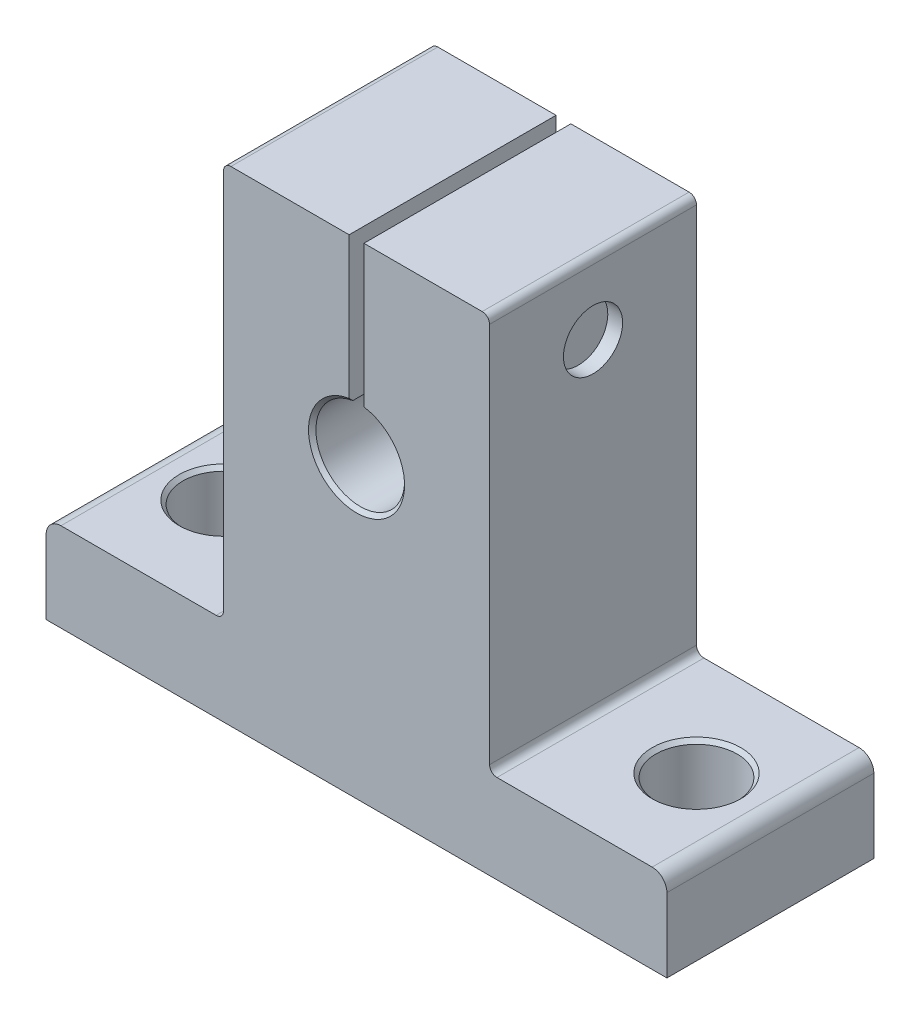
SolidWorks part; units mm, degrees
ref_plane "Front Plane" through (0, 0, 0) normal (0, 0, 1) x (1, 0, 0)
ref_plane "Top Plane" through (0, 0, 0) normal (0, 1, 0) x (1, 0, 0)
ref_plane "Right Plane" through (0, 0, 0) normal (1, 0, 0) x (0, 0, -1)
sketch "Sketch1" plane through (0, 0, 0) normal (0, 0, 1) x (1, 0, 0)
  line L0 (-21, 0) -> (21, 0)
  line L1 (-21, 0) -> (-21, 6)
  line L2 (-21, 6) -> (-9, 6)
  line L3 (-9, 6) -> (-9, 32.8)
  line L4 (-9, 32.8) -> (-0.5, 32.8)
  line L5 (9, 32.8) -> (9, 6)
  line L6 (9, 6) -> (21, 6)
  line L7 (21, 6) -> (21, 0)
  line L8 (-0.5, 32.8) -> (-0.5, 22.958)
  line L9 (0.5, 32.8) -> (0.5, 22.958)
  line L10 (0.5, 32.8) -> (9, 32.8)
  arc A0 (-0.5, 22.958) -> (0.5, 22.958) centre (0, 20) ccw
  point P11 (0, 0)
  point P13 (-0.5, 27.879)
  dimension "D6" = 3
  dimension "D1" = 42
  dimension "D2" = 6
  dimension "D3" = 20
  dimension "D4" = 32.8
  dimension "D5" = 1
  dimension "D7" = 18
extrude "Boss-Extrude1" add sketch "Sketch1" along normal blind 14
sketch "Sketch3" plane through (0, 0, 0) normal (0, -1, 0) x (1, 0, 0)
  line L0 (-16, 7) -> (16, 7) construction
  line L1 (-21, 14) -> (-21, 0) construction
  circle A0 centre (-16, 7) radius 2.75
  circle A1 centre (16, 7) radius 2.75
  point P2 (0, 7)
  point P7 (-21, 7)
  dimension "D2" = 5.5
  dimension "D1" = 32
extrude "Cut-Extrude1" cut sketch "Sketch3" against normal blind 6 and the other way through all
fillet "Fillet1" radius 1 2 edges at (21, 6, 7) (-21, 6, 7)
fillet "Fillet2" radius 0.5 4 edges at (-9, 32.8, 7) (9, 32.8, 7) (9, 6, 7) (-9, 6, 7)
chamfer "Chamfer1" distance 0.25 6 edges at (-16, 0, 9.75) (16, 0, 9.75) (18.75, 6, 7) (-13.25, 6, 7) (0, 17, 0) (0, 17, 14)
sketch "Sketch4" plane through (-9, 0, 0) normal (-1, 0, 0) x (0, 0, 1)
  line L0 (14, 32.3) -> (0, 32.3) construction
  line L1 (0, 32.8) -> (14, 32.8) construction
  circle A0 centre (7, 27.9) radius 3.1
  point P6 (7, 32.3)
  dimension "D1" = 6.2
  dimension "D2" = 4.9
extrude "Cut-Extrude2" cut sketch "Sketch4" against normal blind 1
sketch "Sketch5" plane through (-8, 0, 0) normal (-1, 0, 0) x (0, 0, 1)
  circle A0 centre (7, 27.9) radius 3.1
  circle A1 centre (7, 27.9) radius 3
  dimension "D1" = 6
  dimension "D2" = 6.2
extrude "Cut-Extrude3" cut sketch "Sketch5" against normal blind 4
chamfer "Chamfer2" distance 0.2 1 edges at (-8, 24.9, 7)
sketch "Sketch6" plane through (-8, 0, 0) normal (-1, 0, 0) x (0, 0, 1)
  line L1 (7.1145, 29.6283) -> (5.5605, 28.8633)
  line L2 (5.5605, 28.8633) -> (5.446, 27.135)
  line L3 (5.446, 27.135) -> (6.8855, 26.1717)
  line L4 (6.8855, 26.1717) -> (8.4395, 26.9367)
  line L5 (8.4395, 26.9367) -> (8.554, 28.665)
  line L6 (8.554, 28.665) -> (7.1145, 29.6283)
  circle A0 centre (7, 27.9) radius 1.5 construction
  dimension "D1" = 3
extrude "Cut-Extrude4" cut sketch "Sketch6" against normal blind 2
sketch "Sketch7" plane through (-0.5, 0, 0) normal (1, 0, 0) x (0, 0, -1)
  circle A0 centre (-7, 27.9) radius 2
  dimension "D1" = 4
extrude "Boss-Extrude2" add sketch "Sketch7" along normal blind 1
sketch "Sketch8" plane through (9, 0, 0) normal (1, 0, 0) x (0, 0, -1)
  circle A0 centre (-7, 27.9) radius 2
  dimension "D1" = 4
extrude "Cut-Extrude5" cut sketch "Sketch8" against normal blind 1
sketch "Sketch9" plane through (-8, 0, 0) normal (-1, 0, 0) x (0, 0, 1)
  circle A0 centre (7, 27.9) radius 1.7321
extrude "Cut-Extrude6" cut sketch "Sketch9" against normal blind 1 draft 45
equation "\"h\"= 20'6"
equation "\"w\"= 42'1"
equation "\"l\"= 14'3"
equation "\"f\"= 32.8'2"
equation "\"g\"= 6'9"
equation "\"p\"= 18'5"
equation "\"b\"= 32'4"
equation "\"s\"= 5.5'10"
equation "\"sk\"= 6'7 dg kinh truc"
equation "\"D1@Sketch1\"=\"w\""
equation "\"D2@Sketch1\"=\"g\""
equation "\"D3@Sketch1\"=\"h\""
equation "\"D4@Sketch1\"=\"f\""
equation "\"rk\"= 1'11 be rong khe"
equation "\"D5@Sketch1\"=\"rk\""
equation "\"D6@Sketch1\"=\"sk\"/2"
equation "\"D1@Boss-Extrude1\"=\"l\""
equation "\"D1@Sketch3\"=\"b\""
equation "\"D2@Sketch3\"=\"s\""
equation "\"D1@Cut-Extrude1\"=\"g\""
equation "\"D7@Sketch1\"=\"p\""
equation "\"bo\"= 1'12 bo goc"
equation "\"D1@Fillet1\"=\"bo\""
equation "\"D1@Fillet2\"=\"bo\"/2"
equation "\"D1@Chamfer1\"=\"bo\"/4"
equation "\"m\"= 4'8 bu long"
equation "\"D1@Sketch4\"=1.5*\"m\"+0.2"
equation "\"D1@Sketch5\"=\"m\"*1.5"
equation "\"D2@Sketch5\"=\"m\"*1.5+0.2"
equation "\"D1@Cut-Extrude3\"=\"m\""
equation "\"D1@Chamfer2\"=\"m\"*0.05"
equation "\"D1@Cut-Extrude4\"=\"m\"/2"
equation "\"D1@Sketch6\"=\"m\"*3/4"
equation "\"D1@Sketch7\"=\"m\""
equation "\"D1@Boss-Extrude2\"=\"rk\""
equation "\"D1@Sketch8\"=\"m\""
equation "\"D2@Sketch4\"=(\"f\"-\"h\"-\"sk\"/2)/2"
